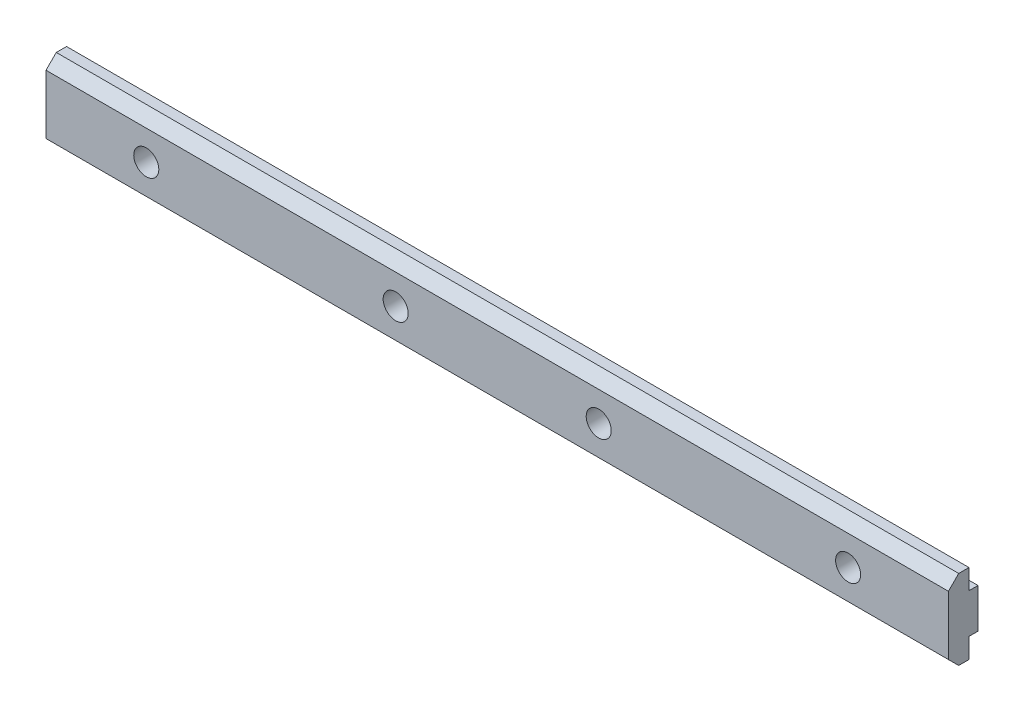
SolidWorks part; units mm, degrees
ref_plane "前视基准面" through (0, 0, 0) normal (0, 0, 1) x (1, 0, 0)
ref_plane "上视基准面" through (0, 0, 0) normal (0, 1, 0) x (1, 0, 0)
ref_plane "右视基准面" through (0, 0, 0) normal (1, 0, 0) x (0, 0, -1)
sketch "草图1" plane through (0, 0, 0) normal (1, 0, 0) x (0, 0, -1)
  line B0 (-4.1, 13.85) -> (-4.1, 2.05)
  line B1 (0, 15.9) -> (-2.05, 15.9)
  line B2 (0, 0) -> (-2.05, 0)
  line B3 (1.8, 4) -> (1.8, 11.9)
  line B4 (0, 0) -> (0, 4)
  line B5 (0, 11.9) -> (0, 15.9)
  line B6 (1.8, 11.9) -> (0, 11.9)
  line B7 (1.8, 4) -> (0, 4)
  line B8 (-2.05, 15.9) -> (-4.1, 13.85)
  line B9 (-2.05, 0) -> (-4.1, 2.05)
sketch_block_instance "A$C4F590A55-1"
sketch_block "A$C4F590A55"
extrude "凸台-拉伸1" add sketch "草图1" along normal mid plane 180
sketch "草图3" plane through (0, 0, -1.8) normal (0, 0, -1) x (-1, 0, 0)
  line L0 (0, 15.9) -> (0, -11.5534) construction
  line L1 (-90, 15.9) -> (90, 15.9) construction
  point P5 (-20.25, 7.95)
  point P6 (-70, 7.95)
  point P7 (70, 7.95)
  point P8 (20.25, 7.95)
  dimension "D1" = 20.25
  dimension "D2" = 70
hole_wizard "M6 螺纹孔1" positions "3D草图1" profile "草图4" tap size "M6" standard "Iso"
sketch3d "3D草图1"
  point P0 (70, 7.95, -1.8)
  point P3 (20.25, 7.95, -1.8)
  point P6 (-20.25, 7.95, -1.8)
  point P9 (-70, 7.95, -1.8)
sketch "草图4" plane through (70, 7.95, -1.8) normal (1, 0, 0) x (0, 1, 0)
  line L0 (0, 0) -> (0, 29.5022)
  line L1 (0, 29.5022) -> (2.5, 28)
  line L2 (2.5, 28) -> (2.5, 0)
  line L5 (2.5, 0) -> (0, 0)
  line L10 (0, 29.5022) -> (-2.5, 28) construction
  line L11 (0, -6.35) -> (0, 107.95) construction
  dimension "螺纹孔钻头直径" = 5
  dimension "螺纹孔钻头深度" = 28
  dimension "导头角度" = 118
cosmetic thread "孔螺蚊线1"
cosmetic thread "孔螺蚊线2"
cosmetic thread "孔螺蚊线3"
cosmetic thread "孔螺蚊线4"
